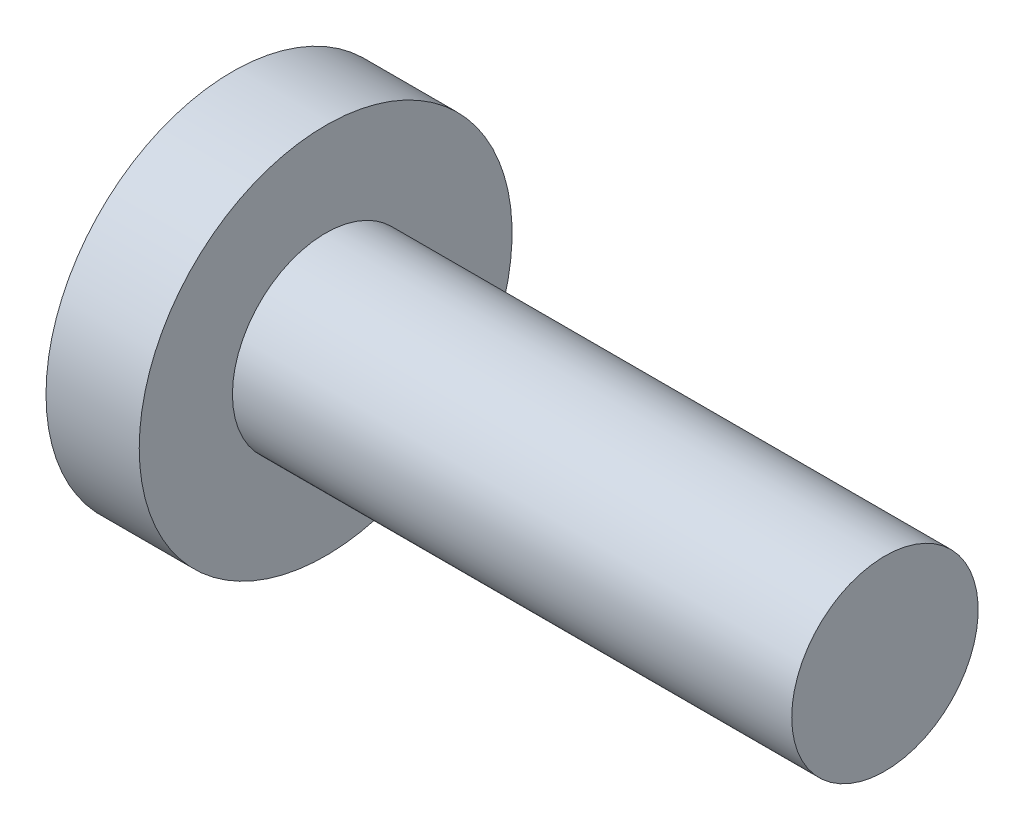
SolidWorks part; units mm, degrees
ref_plane "Plano frontal" through (0, 0, 0) normal (0, 0, 1) x (1, 0, 0)
ref_plane "Plano superior" through (0, 0, 0) normal (0, 1, 0) x (1, 0, 0)
ref_plane "Plano direito" through (0, 0, 0) normal (1, 0, 0) x (0, 0, -1)
sketch "Esboço1" plane through (0, 0, 0) normal (0, 0, 1) x (1, 0, 0)
  line L0 (0, 0) -> (35, 0) construction
  line L1 (0, 0) -> (0, 10)
  line L2 (0, 10) -> (5, 10)
  line L3 (5, 10) -> (5, 5)
  line L4 (5, 5) -> (35, 5)
  line L5 (35, 5) -> (35, 0)
  line L6 (35, 0) -> (0, 0)
  point P5 (0, 0)
  dimension "D1" = 5
  dimension "D2" = 30
  dimension "D3" = 10
  dimension "D4" = 5
revolve "Revolução1" add sketch "Esboço1" angle 360 about L0
